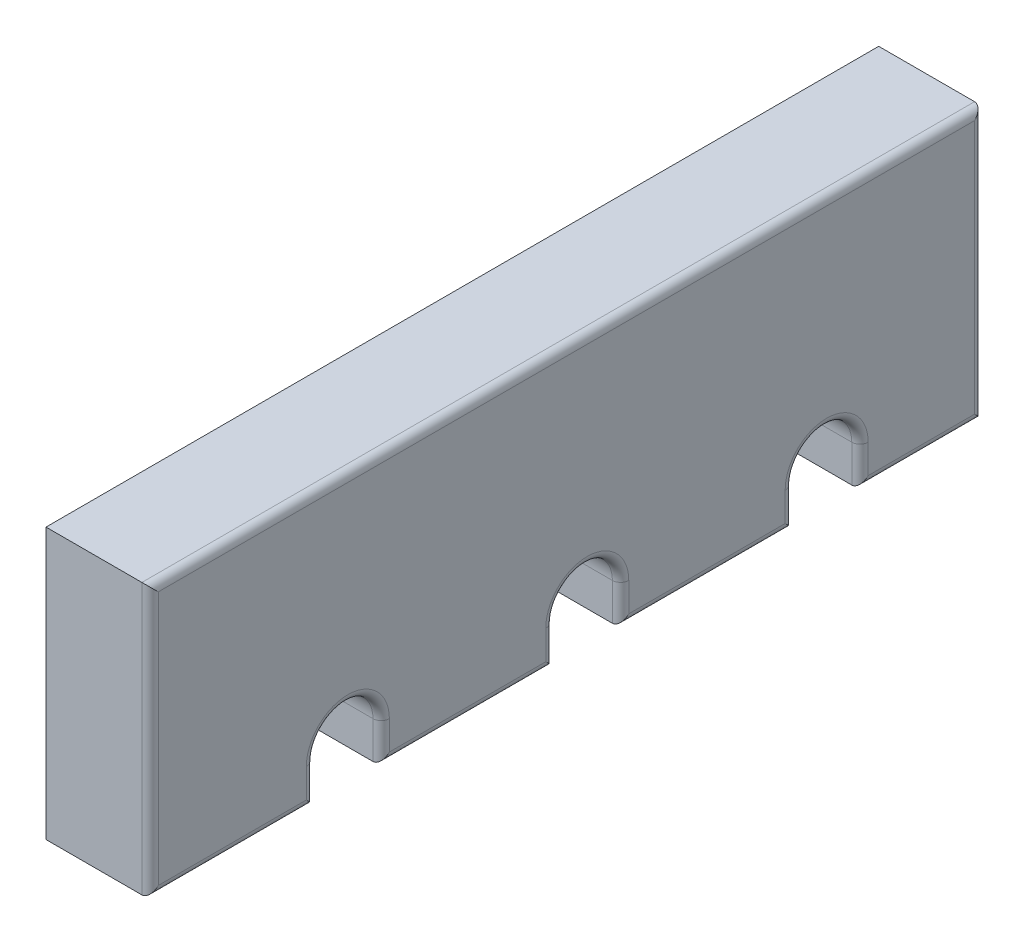
SolidWorks part; units mm, degrees
ref_plane "Front Plane" through (0, 0, 0) normal (0, 0, 1) x (1, 0, 0)
ref_plane "Top Plane" through (0, 0, 0) normal (0, 1, 0) x (1, 0, 0)
ref_plane "Right Plane" through (0, 0, 0) normal (1, 0, 0) x (0, 0, -1)
sketch "Sketch1" plane through (0, 0, 0) normal (1, 0, 0) x (0, 0, -1)
  line L0 (-243.84, 72.39) -> (243.84, 72.39) construction
  line L1 (-254, 82.55) -> (254, 82.55)
  line L2 (-254, 82.55) -> (-254, -82.55)
  line L3 (-254, -82.55) -> (254, -82.55)
  line L4 (254, 82.55) -> (254, -82.55)
  line L5 (-254, 82.55) -> (254, -82.55) construction
  line L6 (-254, -82.55) -> (254, 82.55) construction
  line L7 (243.84, 72.39) -> (243.84, -72.39) construction
  line L8 (-243.84, -72.39) -> (243.84, -72.39) construction
  line L9 (-243.84, 72.39) -> (-243.84, -72.39) construction
  point P0 (0, 0)
  point P10 (-136.43, 72.39)
  point P11 (-243.84, 72.39)
  point P12 (157.47, 72.39)
  point P13 (95.71, -72.39)
  point P14 (243.84, 72.39)
  point P15 (243.84, -72.39)
  point P16 (-65.23, -72.39)
  point P18 (-243.84, -72.39)
  dimension "D1" = 508
  dimension "D2" = 165.1
  dimension "D4" = 107.41
  dimension "D5" = 86.37
  dimension "D6" = 178.61
  dimension "D7" = 148.13
  dimension "D3" = 10.16
extrude "Boss-Extrude2" add sketch "Sketch1" along normal blind 63.5
sketch "Sketch14" plane through (63.5, 0, 0) normal (1, 0, 0) x (0, 0, -1)
  line L0 (-133.35, -82.55) -> (-133.35, -59.9) construction
  line L1 (-254, -82.55) -> (254, -82.55) construction
  line L2 (-153.67, -82.55) -> (-153.67, -59.9)
  line L3 (-113.03, -82.55) -> (-113.03, -59.9)
  line L4 (-254, 82.55) -> (-254, -82.55) construction
  line L5 (12.7, -82.55) -> (12.7, -59.9) construction
  line L6 (-7.62, -82.55) -> (-7.62, -59.9)
  line L7 (33.02, -82.55) -> (33.02, -59.9)
  line L8 (158.75, -82.55) -> (158.75, -59.9) construction
  line L9 (138.43, -82.55) -> (138.43, -59.9)
  line L10 (179.07, -82.55) -> (179.07, -59.9)
  arc A0 (-153.67, -82.55) -> (-113.03, -82.55) centre (-133.35, -82.55) ccw
  arc A1 (-113.03, -59.9) -> (-153.67, -59.9) centre (-133.35, -59.9) ccw
  arc A2 (-7.62, -82.55) -> (33.02, -82.55) centre (12.7, -82.55) ccw
  arc A3 (33.02, -59.9) -> (-7.62, -59.9) centre (12.7, -59.9) ccw
  arc A4 (138.43, -82.55) -> (179.07, -82.55) centre (158.75, -82.55) ccw
  arc A5 (179.07, -59.9) -> (138.43, -59.9) centre (158.75, -59.9) ccw
  point P4 (-133.35, -71.225)
  point P15 (12.7, -71.225)
  point P22 (158.75, -71.225)
  dimension "D1" = 22.65
  dimension "D2" = 120.65
  dimension "D3" = 40.64
  dimension "D4" = 3
extrude "Cut-Extrude2" cut sketch "Sketch14" against normal through all
shell "Shell1" thickness 6.35
fillet "Fillet1" radius 5 16 edges at (63.5, -82.55, 203.835) (63.5, 0, 254) (63.5, 82.55, 0) (63.5, 0, -254) (63.5, -82.55, -216.535) (63.5, -71.225, -179.07) (63.5, -39.58, -158.75) (63.5, -71.225, -138.43) (63.5, -82.55, -85.725) (63.5, -71.225, -33.02) (63.5, -39.58, -12.7) (63.5, -71.225, 7.62) (63.5, -82.55, 60.325) (63.5, -71.225, 113.03) (63.5, -39.58, 133.35) (63.5, -71.225, 153.67)
fillet "Fillet2" radius 3.18 16 edges at (57.15, -33.23, 133.35) (57.15, -68.05, 106.68) (57.15, -76.2, 60.325) (57.15, -68.05, 13.97) (57.15, -33.23, -12.7) (57.15, -68.05, -39.37) (57.15, -76.2, -85.725) (57.15, -68.05, -132.08) (57.15, -33.23, -158.75) (57.15, -68.05, -185.42) (57.15, -76.2, -216.535) (57.15, 0, -247.65) (57.15, 76.2, 0) (57.15, 0, 247.65) (57.15, -76.2, 203.835) (57.15, -68.05, 160.02)
